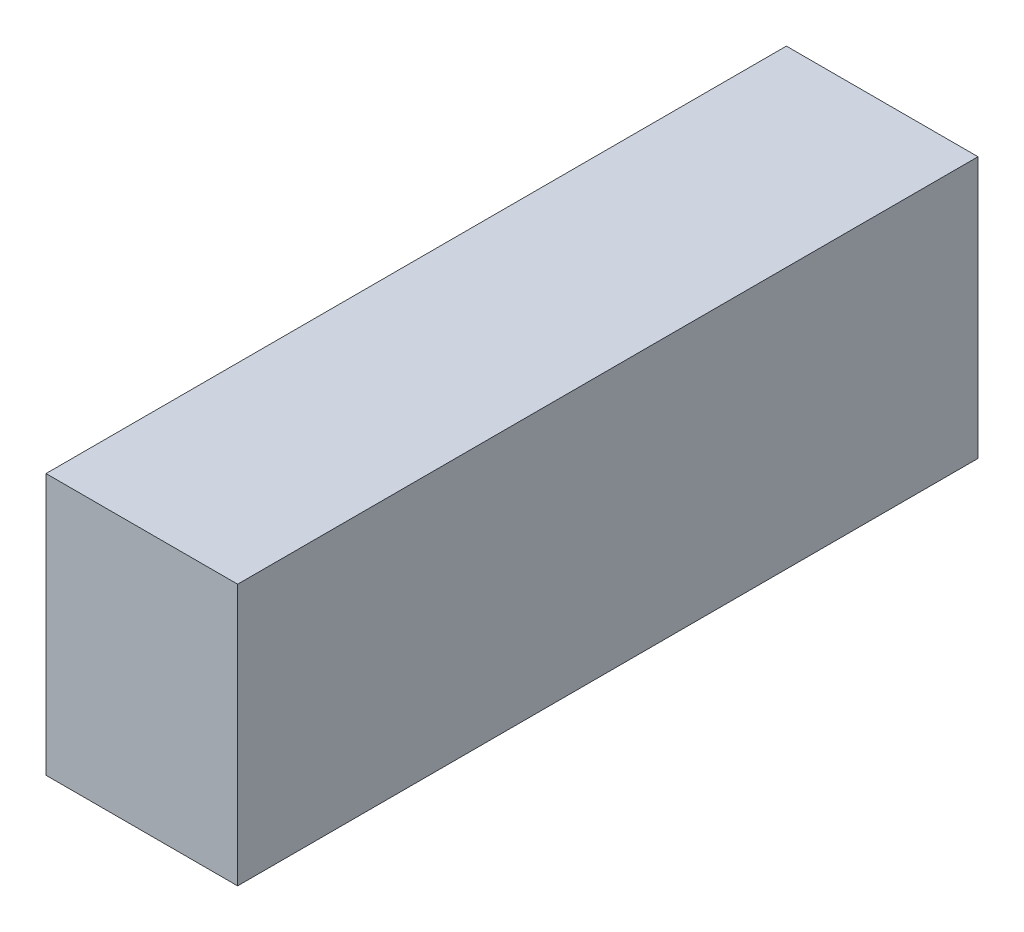
SolidWorks part; units mm, degrees
ref_plane "Front Plane" through (0, 0, 0) normal (0, 0, 1) x (1, 0, 0)
ref_plane "Top Plane" through (0, 0, 0) normal (0, 1, 0) x (1, 0, 0)
ref_plane "Right Plane" through (0, 0, 0) normal (1, 0, 0) x (0, 0, -1)
sketch "Sketch1" plane through (0, 0, 0) normal (0, 0, 1) x (1, 0, 0)
  line L1 (-13.97, -19.05) -> (13.97, -19.05)
  line L2 (-13.97, -19.05) -> (-13.97, 19.05)
  line L3 (-13.97, 19.05) -> (13.97, 19.05)
  line L4 (13.97, -19.05) -> (13.97, 19.05)
  line L5 (-13.97, -19.05) -> (13.97, 19.05) construction
  line L6 (-13.97, 19.05) -> (13.97, -19.05) construction
  point P0 (0, 0)
  dimension "D1" = 38.1
  dimension "D2" = 27.94
extrude "Boss-Extrude1" add sketch "Sketch1" along normal blind 31.75
sketch "Sketch2" plane through (0, 0, 0) normal (0, 0, -1) x (-1, 0, 0)
  line L0 (13.97, -19.05) -> (-13.97, -19.05) construction
  line L1 (-13.97, 19.05) -> (13.97, 19.05)
  line L2 (-13.97, 19.05) -> (-13.97, -19.05)
  line L3 (-13.97, -19.05) -> (13.97, -19.05)
  line L4 (13.97, 19.05) -> (13.97, -19.05)
  dimension "D1" = 27.94
extrude "Boss-Extrude2" add sketch "Sketch2" along normal blind 76.2
